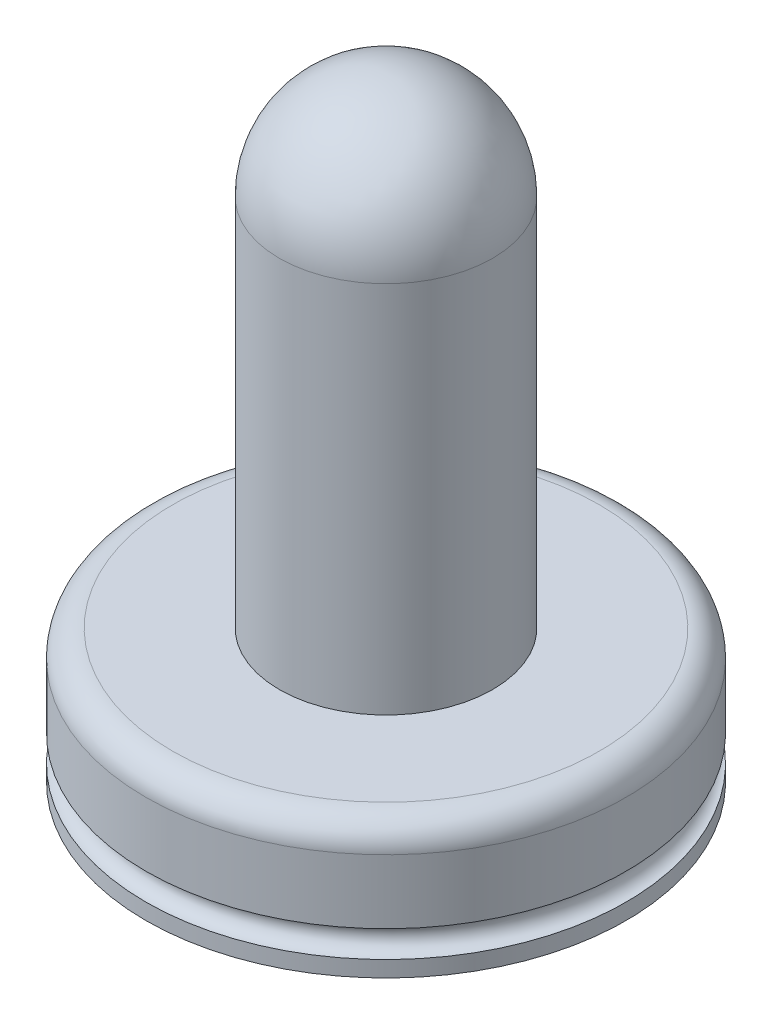
SolidWorks part; units mm, degrees
material "SUS304"
ref_plane "Front Plane" through (0, 0, 0) normal (0, 0, 1) x (1, 0, 0)
ref_plane "Top Plane" through (0, 0, 0) normal (0, 1, 0) x (1, 0, 0)
ref_plane "Right Plane" through (0, 0, 0) normal (1, 0, 0) x (0, 0, -1)
sketch "Sketch1" plane through (0, 0, 0) normal (0, 0, 1) x (1, 0, 0)
  line L0 (0, 0) -> (0, 23) construction
  line L1 (4, 19) -> (4, 5)
  line L2 (4, 5) -> (8, 5)
  line L3 (9, 4) -> (9, 1.6)
  line L4 (9, 0.6) -> (9, 0)
  arc A0 (4, 19) -> (0, 23) centre (0, 19) ccw
  arc A1 (9, 1.6) -> (9, 0.6) centre (9, 1.1) ccw
  arc A2 (8, 5) -> (9, 4) centre (8, 4) cw
  point P13 (9, 5)
  dimension "D1" = 4
  dimension "D6" = 0.5
  dimension "D7" = 1
  dimension "D2" = 18
  dimension "D3" = 18
  dimension "D4" = 5
  dimension "D5" = 0.6
revolve "Revolve-Thin1" add sketch "Sketch1" angle 360 about L0
equation "\"Mass Kg\"= \"SW-Mass\""
